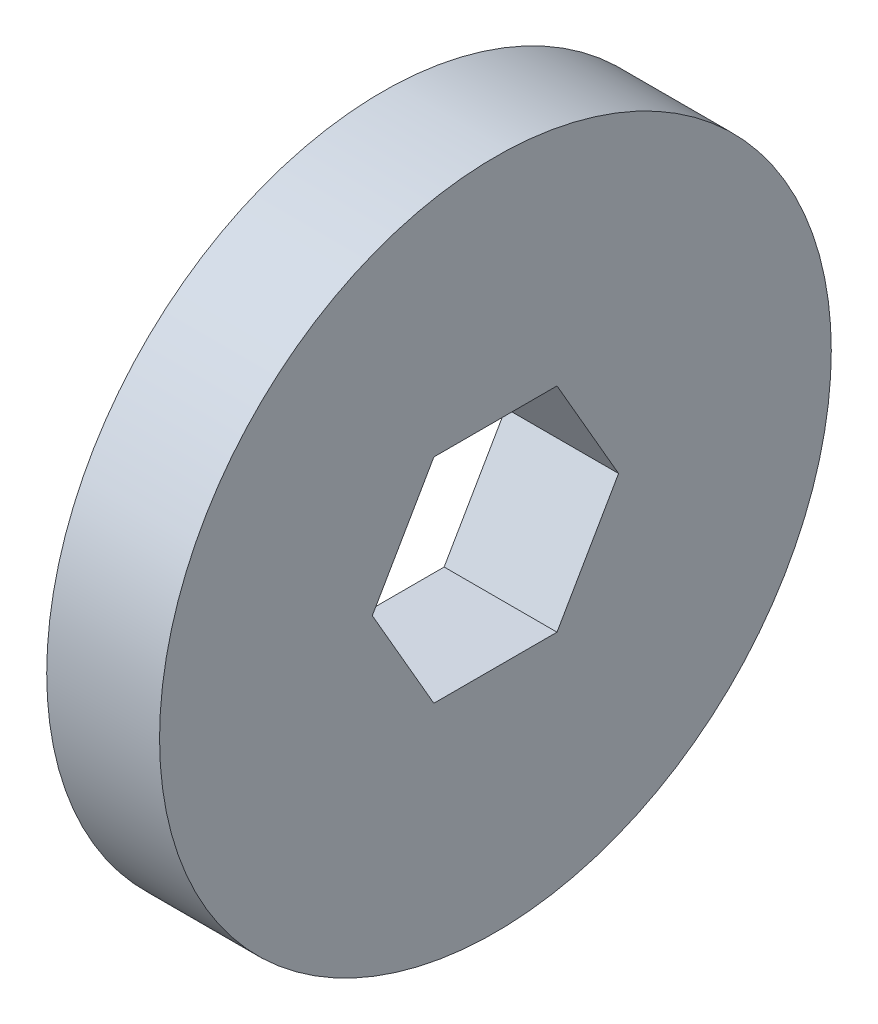
SolidWorks part; units mm, degrees
ref_plane "Alzado" through (0, 0, 0) normal (0, 0, 1) x (1, 0, 0)
ref_plane "Planta" through (0, 0, 0) normal (0, 1, 0) x (1, 0, 0)
ref_plane "Vista lateral" through (0, 0, 0) normal (1, 0, 0) x (0, 0, -1)
sketch "Croquis1" plane through (0, 0, 0) normal (1, 0, 0) x (0, 0, -1)
  line L1 (7.3323, 0) -> (3.6662, 6.35)
  line L2 (3.6662, 6.35) -> (-3.6662, 6.35)
  line L3 (-3.6662, 6.35) -> (-7.3323, 0)
  line L4 (-7.3323, 0) -> (-3.6662, -6.35)
  line L5 (-3.6662, -6.35) -> (3.6662, -6.35)
  line L6 (3.6662, -6.35) -> (7.3323, 0)
  circle A0 centre (0, 0) radius 20
  circle A1 centre (0, 0) radius 6.35 construction
  dimension "D1" = 40
  dimension "D2" = 12.7
extrude "Saliente-Extruir1" add sketch "Croquis1" along normal blind 6.72
